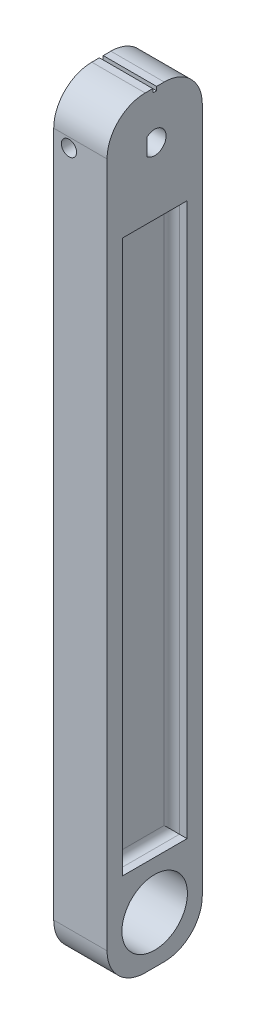
SolidWorks part; units mm, degrees
ref_plane "Alzado" through (0, 0, 0) normal (0, 0, 1) x (1, 0, 0)
ref_plane "Planta" through (0, 0, 0) normal (0, 1, 0) x (1, 0, 0)
ref_plane "Vista lateral" through (0, 0, 0) normal (1, 0, 0) x (0, 0, -1)
sketch "Croquis1" plane through (0, 0, 0) normal (0, 1, 0) x (1, 0, 0)
  line L1 (0, 0) -> (14, 0)
  line L2 (0, 0) -> (0, 25)
  line L3 (0, 25) -> (14, 25)
  line L4 (14, 0) -> (14, 25)
  dimension "D1" = 14
  dimension "D2" = 25
extrude "Saliente-Extruir1" add sketch "Croquis1" along normal blind 200
fillet "Redondeo1" radius 10 1 edges at (7, 0, -25)
fillet "Redondeo2" radius 10 1 edges at (7, 0, 0)
sketch "Croquis2" plane through (14, 0, 0) normal (1, 0, 0) x (0, 0, -1)
  line L0 (0, 200) -> (25, 200) construction
  line L1 (25, 200) -> (25, 10) construction
  line L2 (10.5, 185.2639) -> (10.5, 189.7361)
  arc A0 (10.5, 185.2639) -> (10.5, 189.7361) centre (12.5, 187.5) ccw
  circle A1 centre (12.5, 12.5) radius 8.6
  dimension "D2" = 6
  dimension "D5" = 17.2
  dimension "D1" = 12.5
  dimension "D3" = 12.5
  dimension "D4" = 175
  dimension "D6" = 12.5
  dimension "D7" = 2
extrude "Cortar-Extruir1" cut sketch "Croquis2" against normal blind 28
sketch "Croquis14" plane through (14, 0, 0) normal (1, 0, 0) x (0, 0, -1)
  line L0 (10.5, 185.2639) -> (10.5, 189.7361)
  circle A0 centre (12.5, 187.5) radius 9.913
  arc A1 (10.5, 185.2639) -> (10.5, 189.7361) centre (12.5, 187.5) ccw
  dimension "D1" = 6
  dimension "D2" = 2
extrude "Saliente-Extruir2" add sketch "Croquis14" against normal up to surface (14 mm away) up to face at (0, 187.5, -13)
sketch "Croquis12" plane through (0, 0, -25) normal (0, 0, -1) x (-1, 0, 0)
  line L1 (-14, 200) -> (0, 200) construction
  line L2 (0, 200) -> (0, 10) construction
  circle A0 centre (-4, 187.5) radius 2
  dimension "D1" = 4
  dimension "D2" = 4
  dimension "D3" = 12.5
extrude "Cortar-Extruir7" cut sketch "Croquis12" against normal through all
sketch "Croquis15" plane through (0, 0, 0) normal (-1, 0, 0) x (0, 0, 1)
  line L1 (-8.0822, 190.3) -> (-5.0822, 190.3)
  line L2 (-8.0822, 190.3) -> (-8.0822, 184.7)
  line L3 (-8.0822, 184.7) -> (-5.0822, 184.7)
  line L4 (-5.0822, 190.3) -> (-5.0822, 184.7)
  dimension "D1" = 5.6
  dimension "D2" = 3
extrude "Cortar-Extruir9" cut sketch "Croquis15" against normal blind 8
sketch "Croquis16" plane through (0, 0, 0) normal (-1, 0, 0) x (0, 0, 1)
  line L0 (0, 200) -> (0, 10) construction
  line L1 (-21, 170) -> (-4, 170)
  line L2 (-21, 170) -> (-21, 25)
  line L3 (-21, 25) -> (-4, 25)
  line L4 (-4, 170) -> (-4, 25)
  line L5 (-25, 200) -> (-25, 10) construction
  line L6 (-25, 200) -> (0, 200) construction
  line L7 (-15, 0) -> (-10, 0) construction
  dimension "D1" = 4
  dimension "D2" = 4
  dimension "D3" = 30
  dimension "D4" = 25
extrude "Cortar-Extruir10" cut sketch "Croquis16" against normal blind 4
sketch "Croquis17" plane through (14, 0, 0) normal (1, 0, 0) x (0, 0, -1)
  line L0 (10, 0) -> (15, 0) construction
  line L1 (21, 170) -> (4, 170)
  line L2 (21, 170) -> (21, 25)
  line L3 (21, 25) -> (4, 25)
  line L4 (4, 170) -> (4, 25)
  line L5 (0, 200) -> (25, 200) construction
  line L6 (0, 200) -> (0, 10) construction
  line L7 (25, 200) -> (25, 10) construction
  dimension "D1" = 25
  dimension "D2" = 30
  dimension "D3" = 4
  dimension "D4" = 4
extrude "Cortar-Extruir11" cut sketch "Croquis17" against normal blind 4
fillet "Redondeo5" radius 2 4 edges at (4, 97.5, -21) (4, 170, -12.5) (4, 97.5, -4) (4, 25, -12.5)
fillet "Redondeo6" radius 2 4 edges at (10, 25, -12.5) (10, 97.5, -4) (10, 170, -12.5) (10, 97.5, -21)
sketch "Croquis18" plane through (14, 0, 0) normal (1, 0, 0) x (0, 0, -1)
  line L0 (0, 200) -> (25, 200) construction
  line L1 (12, 200) -> (13, 200)
  line L2 (12, 200) -> (12, 199)
  line L3 (12, 199) -> (13, 199)
  line L4 (13, 200) -> (13, 199)
  point P6 (12.5, 187.5)
  point P7 (12.5, 199)
  dimension "D1" = 1
  dimension "D2" = 1
extrude "Cortar-Extruir12" cut sketch "Croquis18" against normal through all
fillet "Redondeo9" radius 10 1 edges at (7, 200, 0)
fillet "Redondeo10" radius 10 1 edges at (7, 200, -25)
